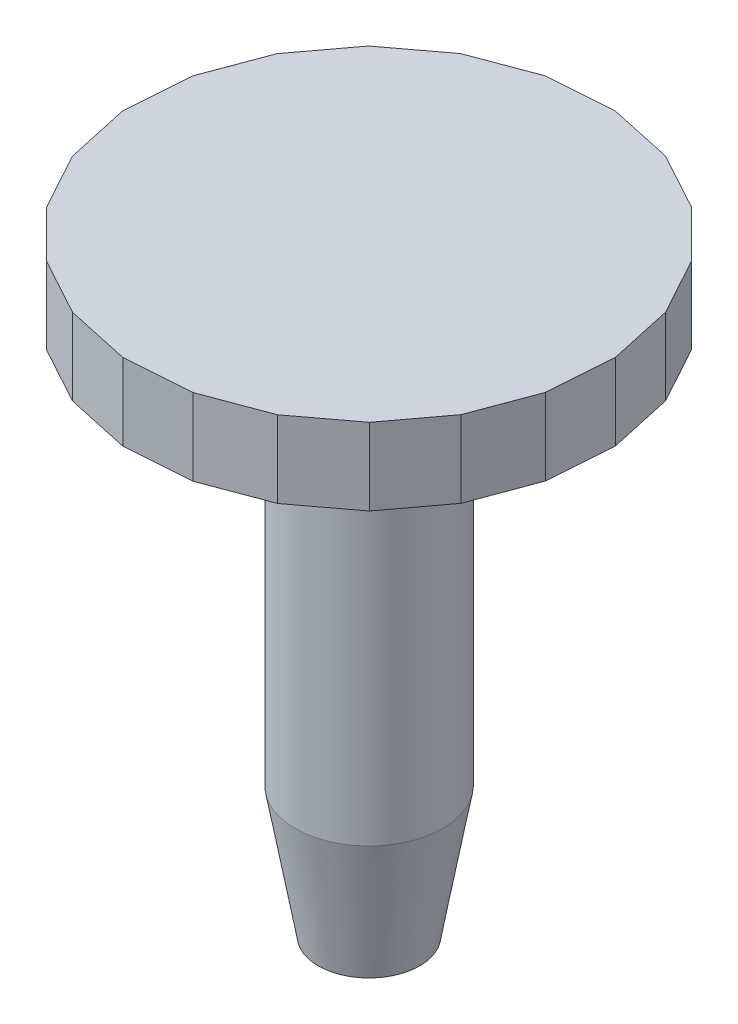
SolidWorks part; units mm, degrees
ref_plane "Front Plane" through (0, 0, 0) normal (0, 0, 1) x (1, 0, 0)
ref_plane "Top Plane" through (0, 0, 0) normal (0, 1, 0) x (1, 0, 0)
ref_plane "Right Plane" through (0, 0, 0) normal (1, 0, 0) x (0, 0, -1)
sketch "Sketch1" plane through (0, 0, 0) normal (0, 1, 0) x (1, 0, 0)
  circle A0 centre (0, 0) radius 3.048
  dimension "D1" = 6.096
extrude "Boss-Extrude1" add sketch "Sketch1" against normal blind 5.3975 draft 10
sketch "Sketch3" plane through (0, 0, 0) normal (0, 1, 0) x (1, 0, 0)
  circle A0 centre (0, 0) radius 3.048
extrude "Boss-Extrude2" add sketch "Sketch3" along normal blind 14.986
sketch "Sketch4" plane through (0, 14.986, 0) normal (0, 1, 0) x (1, 0, 0)
  circle A0 centre (0, 0) radius 3.048
extrude "Boss-Extrude3" add sketch "Sketch4" along normal blind 1.5875 draft 75 contours A0 draft outward yes
sketch "Sketch6" plane through (0, 16.5735, 0) normal (0, 1, 0) x (1, 0, 0)
  line L1 (3.318, 8.9284) -> (0.6681, 9.5015)
  line L2 (0.6681, 9.5015) -> (-2.0358, 9.3049)
  line L3 (-2.0358, 9.3049) -> (-4.5748, 8.3544)
  line L4 (-4.5748, 8.3544) -> (-6.7432, 6.7271)
  line L5 (-6.7432, 6.7271) -> (-8.3653, 4.5548)
  line L6 (-8.3653, 4.5548) -> (-9.3097, 2.0136)
  line L7 (-9.3097, 2.0136) -> (-9.4999, -0.6909)
  line L8 (-9.4999, -0.6909) -> (-8.9205, -3.3393)
  line L9 (-8.9205, -3.3393) -> (-7.6183, -5.7172)
  line L10 (-7.6183, -5.7172) -> (-5.699, -7.632)
  line L11 (-5.699, -7.632) -> (-3.318, -8.9284)
  line L12 (-3.318, -8.9284) -> (-0.6681, -9.5015)
  line L13 (-0.6681, -9.5015) -> (2.0358, -9.3049)
  line L14 (2.0358, -9.3049) -> (4.5748, -8.3544)
  line L15 (4.5748, -8.3544) -> (6.7432, -6.7271)
  line L16 (6.7432, -6.7271) -> (8.3653, -4.5548)
  line L17 (8.3653, -4.5548) -> (9.3097, -2.0136)
  line L18 (9.3097, -2.0136) -> (9.4999, 0.6909)
  line L19 (9.4999, 0.6909) -> (8.9205, 3.3393)
  line L20 (8.9205, 3.3393) -> (7.6183, 5.7172)
  line L21 (7.6183, 5.7172) -> (5.699, 7.632)
  line L22 (5.699, 7.632) -> (3.318, 8.9284)
  circle A1 centre (0, 0) radius 9.428 construction
extrude "Boss-Extrude5" add sketch "Sketch6" along normal blind 3.175
